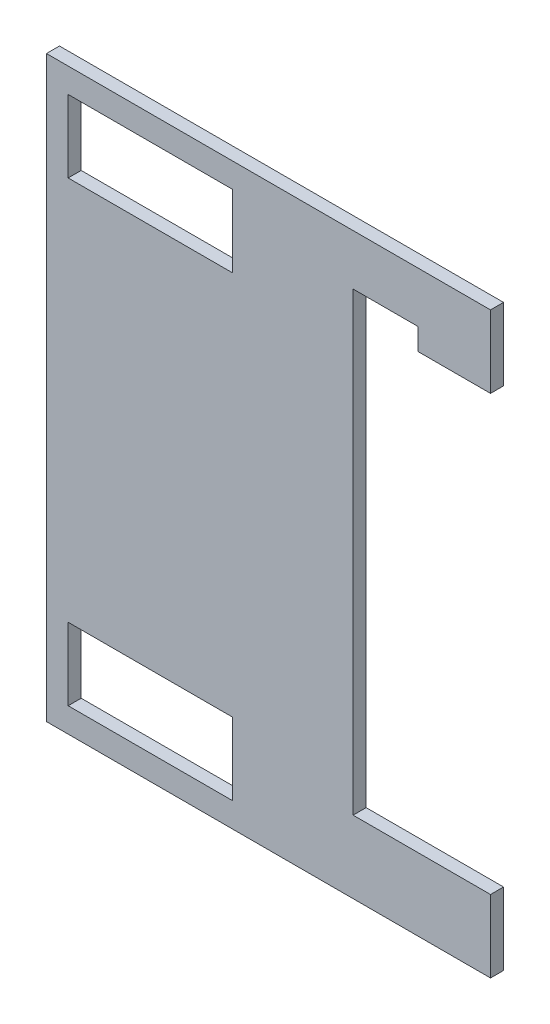
SolidWorks part; units mm, degrees
material "Pine"
ref_plane "Front Plane" through (0, 0, 0) normal (0, 0, 1) x (1, 0, 0)
ref_plane "Top Plane" through (0, 0, 0) normal (0, 1, 0) x (1, 0, 0)
ref_plane "Right Plane" through (0, 0, 0) normal (1, 0, 0) x (0, 0, -1)
sketch "Sketch1" plane through (0, 0, 0) normal (0, 0, 1) x (1, 0, 0)
  line L0 (-16.8129, -74.6) -> (-16.8129, 325.4)
  line L1 (-16.8129, 325.4) -> (-323.8122, 325.4)
  line L2 (-323.8122, 325.4) -> (-323.8122, -74.6)
  line L3 (-323.8122, -74.6) -> (-16.8129, -74.6)
  line L9 (-308.8122, 308.4) -> (-195.1729, 308.4)
  line L10 (-308.8122, 308.4) -> (-308.8122, 258.4)
  line L11 (-308.8122, 258.4) -> (-195.1729, 258.4)
  line L12 (-195.1729, 308.4) -> (-195.1729, 258.4)
  line L13 (-308.8122, 308.4) -> (-195.1729, 258.4) construction
  line L14 (-308.8122, 258.4) -> (-195.1729, 308.4) construction
  line L18 (-308.8122, -57.6) -> (-195.1729, -57.6)
  line L19 (-308.8122, -57.6) -> (-308.8122, -7.6)
  line L20 (-308.8122, -7.6) -> (-195.1729, -7.6)
  line L21 (-195.1729, -57.6) -> (-195.1729, -7.6)
  line L22 (-308.8122, -57.6) -> (-195.1729, -7.6) construction
  line L23 (-308.8122, -7.6) -> (-195.1729, -57.6) construction
  point P16 (-251.9926, 283.4)
  point P27 (-251.9926, -32.6)
  dimension "D2" = 50
  dimension "D3" = 17
  dimension "D5" = 15
  dimension "D6" = 15
extrude "Boss-Extrude1" add sketch "Sketch1" along normal blind 9
sketch "Sketch2" plane through (0, 0, 0) normal (0, 0, -1) x (-1, 0, 0)
  line L0 (111.8129, -24.6) -> (111.8129, 275.4)
  line L1 (16.8129, 325.4) -> (111.8129, 325.4)
  line L2 (16.8129, 325.4) -> (16.8129, 275.4)
  line L3 (16.8129, 275.4) -> (111.8129, 275.4)
  line L4 (111.8129, 325.4) -> (111.8129, 275.4)
  line L5 (16.8129, 325.4) -> (111.8129, 275.4) construction
  line L6 (16.8129, 275.4) -> (111.8129, 325.4) construction
  line L7 (16.8129, -74.6) -> (111.8129, -74.6)
  line L8 (16.8129, -74.6) -> (16.8129, -24.6)
  line L9 (16.8129, -24.6) -> (111.8129, -24.6)
  line L10 (111.8129, -74.6) -> (111.8129, -24.6)
  line L11 (16.8129, -74.6) -> (111.8129, -24.6) construction
  line L12 (16.8129, -24.6) -> (111.8129, -74.6) construction
  point P4 (64.3129, 300.4)
  point P10 (64.3129, -49.6)
  line M11 (16.8129, 325.4) -> (16.8129, -74.6)
  dimension "D1" = 50
  dimension "D2" = 50
  dimension "D3" = 95
extrude "Cut-Extrude1" cut sketch "Sketch2" against normal through all contours L9 L0 L3 M11
sketch "Sketch3" plane through (0, 0, 0) normal (0, 0, -1) x (-1, 0, 0)
  line L1 (111.8129, 275.4) -> (66.8129, 275.4)
  line L2 (111.8129, 275.4) -> (111.8129, 290.4)
  line L3 (111.8129, 290.4) -> (66.8129, 290.4)
  line L4 (66.8129, 275.4) -> (66.8129, 290.4)
  dimension "D1" = 45
  dimension "D2" = 15
extrude "Cut-Extrude2" cut sketch "Sketch3" against normal blind 10
